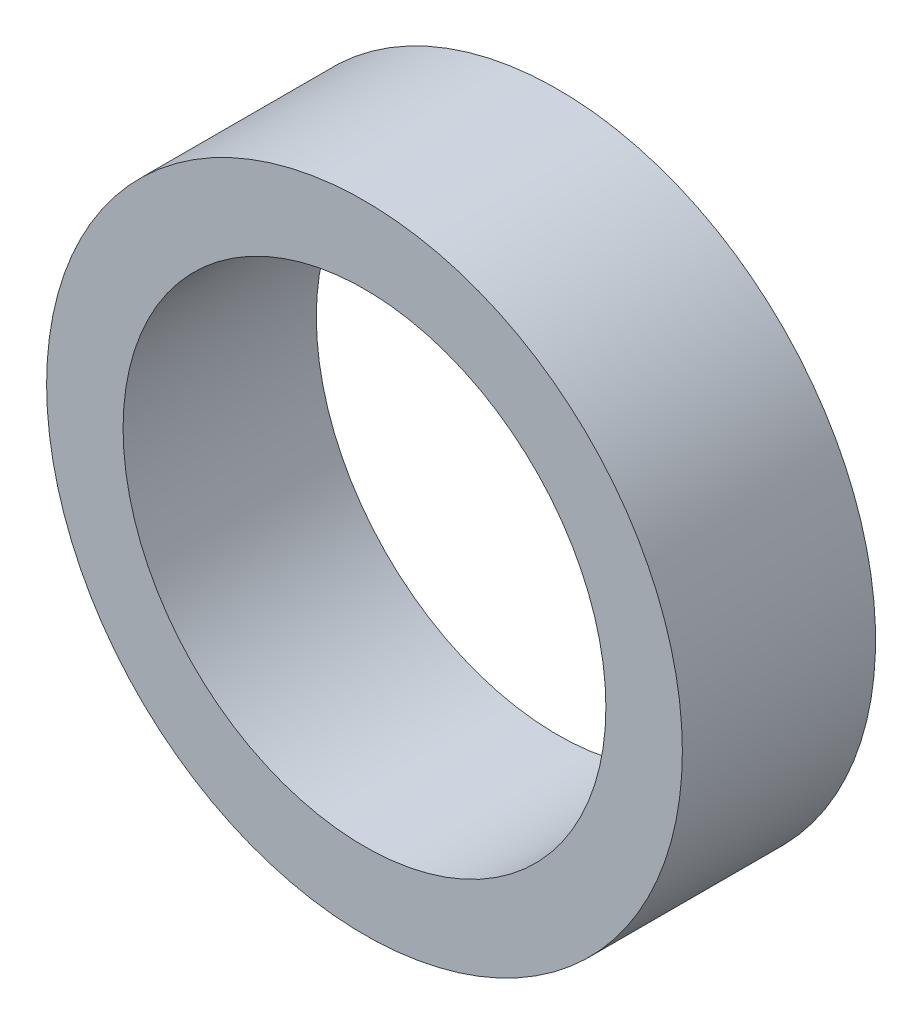
SolidWorks part; units mm, degrees
ref_plane "Front Plane" through (0, 0, 0) normal (0, 0, 1) x (1, 0, 0)
ref_plane "Top Plane" through (0, 0, 0) normal (0, 1, 0) x (1, 0, 0)
ref_plane "Right Plane" through (0, 0, 0) normal (1, 0, 0) x (0, 0, -1)
sketch "Sketch2" plane through (0, 0, 0) normal (0, 0, 1) x (1, 0, 0)
  circle A0 centre (0, 0) radius 6.235
  circle A1 centre (0, 0) radius 8.21
  dimension "D1" = 12.47
  dimension "D2" = 16.42
extrude "Boss-Extrude1" add sketch "Sketch2" along normal blind 6.99
sketch "Sketch3" plane through (0, 0, 6.99) normal (0, 0, 1) x (1, 0, 0)
  circle A0 centre (0, 0) radius 6.235
  circle A1 centre (0, 0) radius 8.21
extrude "Cut-Extrude3" cut sketch "Sketch3" against normal blind 2
sketch "Sketch4" plane through (0, 0, 0) normal (0, 0, -1) x (-1, 0, 0)
  circle A0 centre (0, 0) radius 6.235
  circle A1 centre (0, 0) radius 8.21
extrude "Boss-Extrude2" add sketch "Sketch4" along normal blind 2
sketch "Sketch7" plane through (0, 0, -2) normal (0, 0, -1) x (-1, 0, 0)
  circle A0 centre (0, 0) radius 6.235
  circle A1 centre (0, 0) radius 8.21
extrude "Cut-Extrude4" cut sketch "Sketch7" against normal blind 2
